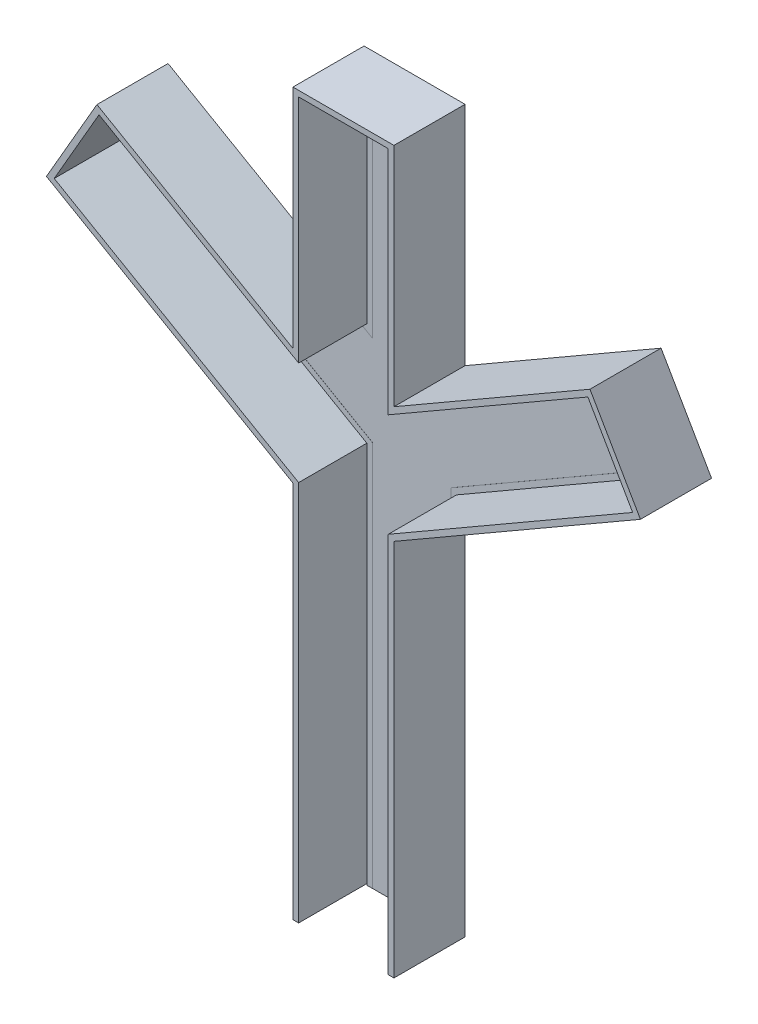
SolidWorks part; units mm, degrees
ref_plane "Спереди" through (0, 0, 0) normal (0, 0, 1) x (1, 0, 0)
ref_plane "Сверху" through (0, 0, 0) normal (0, 1, 0) x (1, 0, 0)
ref_plane "Справа" through (0, 0, 0) normal (1, 0, 0) x (0, 0, -1)
sketch "Sketch1" plane through (0, 0, 0) normal (0, 0, 1) x (1, 0, 0)
  line L0 (-5.5, 17) -> (-5.5, 71.2983)
  line L1 (-5.5, 117) -> (5.5, 117)
  line L2 (-5.5, 84) -> (-34.0788, 100.5)
  line L3 (-34.0788, 100.5) -> (-39.5788, 90.9737)
  line L4 (-39.5788, 90.9737) -> (-5.5, 71.2983)
  line L5 (-5.5, 84) -> (-5.5, 117)
  line L6 (0, 13.8176) -> (0, -11.7579) construction
  line L7 (5.5, 84) -> (5.5, 117)
  line L8 (39.5788, 90.9737) -> (5.5, 71.2983)
  line L9 (34.0788, 100.5) -> (39.5788, 90.9737)
  line L10 (5.5, 84) -> (34.0788, 100.5)
  line L11 (5.5, 17) -> (5.5, 71.2983)
  line L12 (-6.3, 17) -> (-6.3, 70.8364)
  line L13 (-40.6717, 90.6809) -> (-6.3, 70.8364)
  line L14 (-34.3717, 101.5928) -> (-40.6717, 90.6809)
  line L15 (-6.3, 85.3856) -> (-34.3717, 101.5928)
  line L16 (-6.3, 85.3856) -> (-6.3, 117.8)
  line L17 (-6.3, 117.8) -> (6.3, 117.8)
  line L18 (6.3, 85.3856) -> (6.3, 117.8)
  line L19 (6.3, 85.3856) -> (34.3717, 101.5928)
  line L20 (34.3717, 101.5928) -> (40.6717, 90.6809)
  line L21 (40.6717, 90.6809) -> (6.3, 70.8364)
  line L22 (6.3, 17) -> (6.3, 70.8364)
  line L23 (-6.3, 17) -> (-5.5, 17)
  line L24 (5.5, 17) -> (6.3, 17)
  point P15 (0, 117)
  dimension "D1" = 100
  dimension "D2" = 11
  dimension "D3" = 5.5
  dimension "D4" = 60
  dimension "D5" = 90
  dimension "D6" = 33
  dimension "D7" = 0.8
  dimension "D8" = 17
extrude "Boss-Extrude1" add sketch "Sketch1" along normal blind 0.41
sketch "Sketch2" plane through (0, 0, 0) normal (0, 0, 1) x (1, 0, 0)
  line L0 (-5.5, 17) -> (-5.5, 71.2983)
  line L1 (-5.5, 71.2983) -> (-39.5788, 90.9737)
  line L2 (-39.5788, 90.9737) -> (-34.0788, 100.5)
  line L3 (-34.0788, 100.5) -> (-5.5, 84)
  line L4 (-5.5, 84) -> (-5.5, 117)
  line L5 (-5.5, 117) -> (5.5, 117)
  line L6 (5.5, 117) -> (5.5, 84)
  line L7 (5.5, 84) -> (34.0788, 100.5)
  line L8 (34.0788, 100.5) -> (39.5788, 90.9737)
  line L9 (39.5788, 90.9737) -> (5.5, 71.2983)
  line L10 (5.5, 71.2983) -> (5.5, 17)
  line L11 (5.5, 71.2983) -> (5.5, 17) construction
  line L12 (5.5, 17) -> (-5.5, 17)
extrude "Boss-Extrude2" add sketch "Sketch2" along normal blind 0.4
sketch "Sketch3" plane through (0, 0, 0) normal (0, 0, 1) x (1, 0, 0)
  line L0 (-6.3, 17.2) -> (-6.3, 70.8364)
  line L1 (-6.3, 70.8364) -> (-40.6717, 90.6809)
  line L2 (-40.6717, 90.6809) -> (-34.3717, 101.5928)
  line L3 (-34.3717, 101.5928) -> (-6.3, 85.3856)
  line L4 (-6.3, 85.3856) -> (-6.3, 117.8)
  line L5 (-6.3, 117.8) -> (6.3, 117.8)
  line L6 (6.3, 117.8) -> (6.3, 85.3856)
  line L7 (6.3, 85.3856) -> (34.3717, 101.5928)
  line L8 (34.3717, 101.5928) -> (40.6717, 90.6809)
  line L9 (40.6717, 90.6809) -> (6.3, 70.8364)
  line L10 (6.3, 70.8364) -> (6.3, 17.2)
  line L11 (-7.1, 17.2) -> (-7.1, 70.3745)
  line L12 (-7.1, 70.3745) -> (-41.7645, 90.3881)
  line L13 (-41.7645, 90.3881) -> (-34.6645, 102.6856)
  line L14 (-34.6645, 102.6856) -> (-7.1, 86.7713)
  line L15 (-7.1, 86.7713) -> (-7.1, 118.6)
  line L16 (-7.1, 118.6) -> (7.1, 118.6)
  line L17 (7.1, 118.6) -> (7.1, 86.7713)
  line L18 (7.1, 86.7713) -> (34.6645, 102.6856)
  line L19 (34.6645, 102.6856) -> (41.7645, 90.3881)
  line L20 (41.7645, 90.3881) -> (7.1, 70.3745)
  line L21 (7.1, 70.3745) -> (7.1, 17.2)
  line L22 (7.1, 70.3745) -> (7.1, 17) construction
  line L23 (6.3, 70.8364) -> (6.3, 17) construction
  line L24 (-7.1, 17.2) -> (-6.3, 17.2)
  line L25 (6.3, 17.2) -> (7.1, 17.2)
  line L26 (-7.1, 17) -> (-7.1, 70.3745) construction
  line L27 (-6.3, 17) -> (-6.3, 70.8364) construction
  dimension "D1" = 0.8
  dimension "D2" = 0.2
extrude "Boss-Extrude3" add sketch "Sketch3" along normal blind 10
